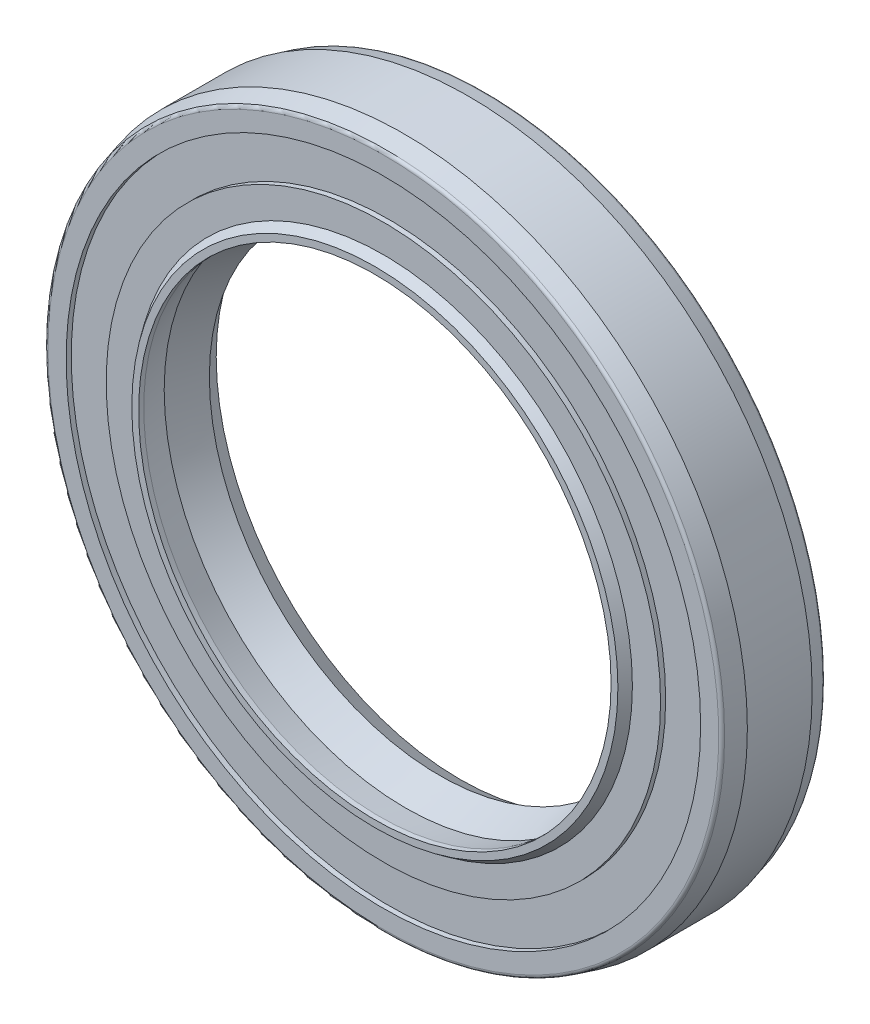
SolidWorks part; units mm, degrees
material "NBR"
ref_plane "Front Plane" through (0, 0, 0) normal (0, 0, 1) x (1, 0, 0)
ref_plane "Top Plane" through (0, 0, 0) normal (0, 1, 0) x (1, 0, 0)
ref_plane "Right Plane" through (0, 0, 0) normal (1, 0, 0) x (0, 0, -1)
sketch "Sketch1" plane through (0, 0, 0) normal (1, 0, 0) x (0, 0, -1)
  line L0 (0, 14.6) -> (0, 16.25)
  line L1 (1.2, 20.14) -> (5, 20.14)
  line L2 (6, 19.8721) -> (6, 18.25)
  line L3 (0, 19.8185) -> (1.2, 20.14)
  line L4 (6, 18.25) -> (5.5, 18.25)
  line L5 (4.5, 14.3) -> (4.5, 15.3)
  line L6 (2.3, 15.2) -> (2, 15.2)
  line L7 (0, 18.6) -> (0, 19.8185)
  line L8 (0, 0) -> (11.0087, 0) construction
  line L9 (-0.5, 13.85) -> (-0.2, 13.85)
  line L10 (5.5, 18.25) -> (5.5, 17.75)
  line L11 (5, 20.14) -> (6, 19.8721)
  line L12 (4.5, 15.3) -> (4.295, 15.3)
  line L13 (2.4, 17.75) -> (5.5, 17.75)
  line L14 (2, 15.2) -> (2, 17.35)
  line L15 (0, 18.6) -> (0.3, 18.6)
  line L16 (0.3, 18.6) -> (0.3, 16.25)
  line L17 (0.3, 16.25) -> (0, 16.25)
  line L18 (0, 14.6) -> (-0.5, 14.25)
  line L19 (-0.5, 14.25) -> (-0.5, 13.85)
  line L21 (1.3, 14.15) -> (3.2977, 13.5)
  line L22 (4.5, 14.3) -> (3.2977, 13.5)
  line L23 (-0.2, 13.85) -> (1.3, 14.15)
  arc A0 (4.295, 15.3) -> (2.3, 15.2) centre (3.3, 15.2) ccw
  arc A1 (2, 17.35) -> (2.4, 17.75) centre (2.4, 17.35) cw
  dimension "D17" = 0.4
  dimension "D18" = 37.2
  dimension "D5" = 1
  dimension "D10" = 27
  dimension "D14" = 32.4
  dimension "D15" = 1.2
  dimension "D1" = 6
  dimension "D2" = 40.28
  dimension "D3" = 1.5
  dimension "D4" = 1.2
  dimension "D6" = 36.5
  dimension "D7" = 35.5
  dimension "D8" = 30.6
  dimension "D9" = 15
  dimension "D11" = 15
  dimension "D12" = 0.5
  dimension "D13" = 1
  dimension "D16" = 4
  dimension "D19" = 32.5
  dimension "D20" = 29.2
  dimension "D21" = 3.2
  dimension "D22" = 28.6
  dimension "D23" = 1.2023
  dimension "D24" = 6.5
  dimension "D25" = 0.3
  dimension "D26" = 28.5
  dimension "D27" = 27.7
  dimension "D28" = 28.3
  dimension "D29" = 0.3
revolve "Revolve1" add sketch "Sketch1" angle 360 about L8
sketch "Sketch3" plane through (0, 0, -6) normal (0, 0, -1) x (-1, 0, 0)
  line L0 (0, 0) -> (-25.6118, 0) construction
  line L1 (-18.2071, -1.25) -> (-16.3, -1.25)
  line L3 (-18.2071, 1.25) -> (-16.3, 1.25)
  line L4 (-16.3, 1.25) -> (-16.3, -1.25)
  circle A0 centre (0, 0) radius 18.25 construction
  arc A1 (-18.2071, 1.25) -> (-18.2071, -1.25) centre (0, 0) ccw
  dimension "D1" = 16.3
  dimension "D2" = 2.5
extrude "Cut-Extrude1" cut sketch "Sketch3" against normal offset from surface (4.2 mm away) 0.2 up to face at (17.35, 0, -2) offset beyond the face yes
pattern_circular "CirPattern1" count 8 over 360 about axis through (0, 0, 0) along (0, 0, 1) of "Cut-Extrude1"
fillet "Fillet1" radius 0.2 2 edges at (19.8721, 0, -6) (19.8185, 0, 0)
